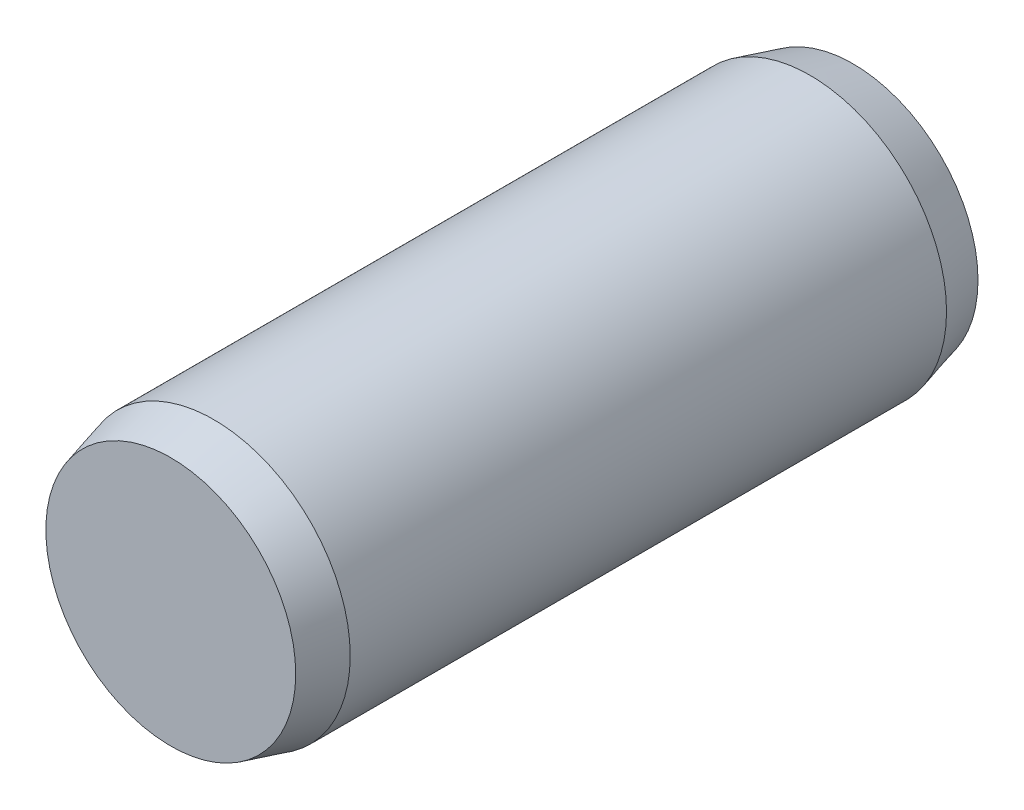
SolidWorks part; units mm, degrees
ref_plane "Front Plane" through (0, 0, 0) normal (0, 0, 1) x (1, 0, 0)
ref_plane "Top Plane" through (0, 0, 0) normal (0, 1, 0) x (1, 0, 0)
ref_plane "Right Plane" through (0, 0, 0) normal (1, 0, 0) x (0, 0, -1)
sketch "Sketch1" plane through (0, 0, 0) normal (1, 0, 0) x (0, 0, -1)
  line L0 (-5, 0) -> (5, 0)
  dimension "Length" = 10
sketch "Sketch2" plane through (0, 0, 0) normal (0, 0, 1) x (1, 0, 0)
  circle A0 centre (0, 0) radius 2
  dimension "Diameter" = 4
sketch "Sketch3" plane through (0, 0, 0) normal (1, 0, 0) x (0, 0, -1)
  line L0 (-5, 0) -> (-5, 1.8312)
  line L1 (-5, 1.8312) -> (-4.37, 2)
  line L2 (-4.37, 2) -> (4.37, 2)
  line L5 (5, 0) -> (-5, 0)
  line L6 (-5, 0) -> (5, 0) construction
  line L7 (-5, 0) -> (5, 0) construction
  line L8 (4.37, 2) -> (5, 1.8312)
  line L9 (5, 1.8312) -> (5, 0)
  point P0 (0, 2)
  dimension "D1" = 15
  dimension "Point Height" = 0.63
revolve "Revolve1" add sketch "Sketch3" angle 360 about L0
